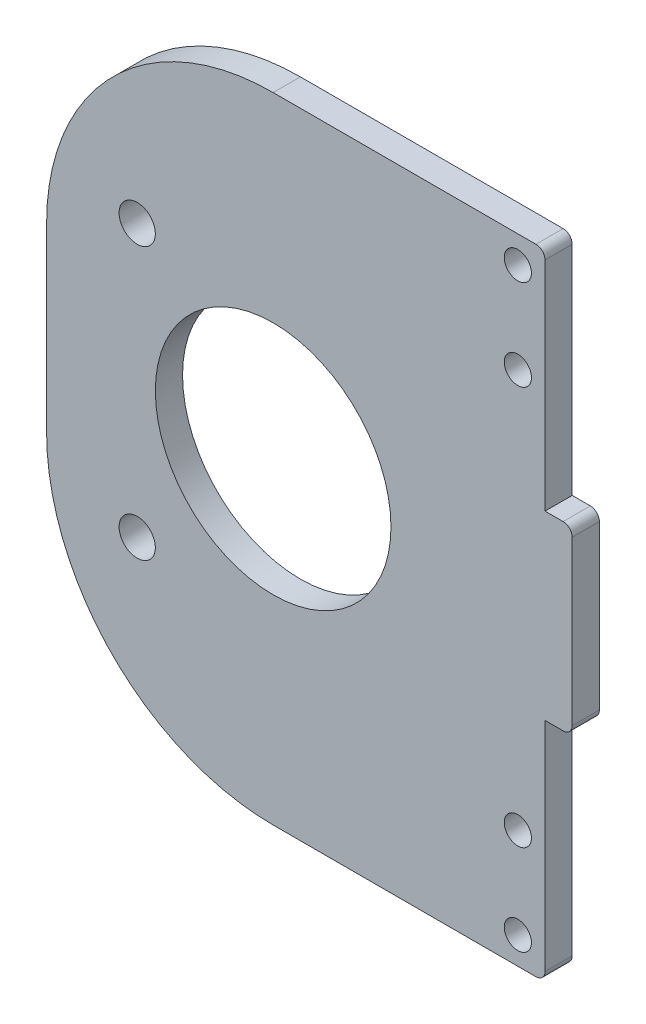
SolidWorks part; units mm, degrees
material "Thornel Mat VMA"
ref_plane "前视基准面" through (0, 0, 0) normal (0, 0, 1) x (1, 0, 0)
ref_plane "上视基准面" through (0, 0, 0) normal (0, 1, 0) x (1, 0, 0)
ref_plane "右视基准面" through (0, 0, 0) normal (1, 0, 0) x (0, 0, -1)
sketch "草图1" plane through (0, 0, 0) normal (0, 0, 1) x (1, 0, 0)
  line L1 (-27.5, -35) -> (27.5, -35)
  line L2 (-27.5, -35) -> (-27.5, 35)
  line L3 (-27.5, 35) -> (27.5, 35)
  line L4 (27.5, -35) -> (27.5, 35)
  line L5 (-27.5, -35) -> (27.5, 35) construction
  line L6 (-27.5, 35) -> (27.5, -35) construction
  point P0 (0, 0)
  dimension "D1" = 55
  dimension "D2" = 70
extrude "凸台-拉伸1" add sketch "草图1" along normal blind 3
sketch "草图3" plane through (0, 0, 0) normal (0, 0, -1) x (-1, 0, 0)
  line L0 (-27.5, 0) -> (27.5, 0) construction
  line L1 (-27.5, -35) -> (-27.5, 35) construction
  line L2 (27.5, 35) -> (27.5, -35) construction
  circle A0 centre (2.5, 0) radius 13
  dimension "D1" = 26
  dimension "D2" = 30
extrude "切除-拉伸1" cut sketch "草图3" against normal through all
sketch "草图4" plane through (0, 0, 3) normal (0, 0, 1) x (1, 0, 0)
  line L0 (-27.5, 0) -> (27.5, 0) construction
  line L1 (-27.5, 35) -> (-27.5, -35) construction
  line L2 (27.5, -35) -> (27.5, 35) construction
  line L3 (27.5, 35) -> (-27.5, 35) construction
  circle A0 centre (24.5, 32) radius 1.5
  circle A1 centre (24.5, 22) radius 1.5
  circle A2 centre (24.5, -22) radius 1.5
  circle A3 centre (24.5, -32) radius 1.5
  dimension "D3" = 3
  dimension "D1" = 3
  dimension "D2" = 3
  dimension "D4" = 10
extrude "切除-拉伸2" cut sketch "草图4" against normal through all
sketch "草图5" plane through (0, 0, 3) normal (0, 0, 1) x (1, 0, 0)
  line L0 (-27.5, 0) -> (27.5, 0) construction
  line L1 (-27.5, 35) -> (-27.5, -35) construction
  line L2 (27.5, -35) -> (27.5, 35) construction
  line L4 (27.5, -10) -> (30.5, -10)
  line L5 (27.5, -10) -> (27.5, 10)
  line L6 (27.5, 10) -> (30.5, 10)
  line L7 (30.5, -10) -> (30.5, 10)
  line L8 (27.5, -10) -> (30.5, 10) construction
  line L9 (27.5, 10) -> (30.5, -10) construction
  point P6 (29, 0)
  dimension "D1" = 3
  dimension "D2" = 20
extrude "凸台-拉伸2" add sketch "草图5" against normal blind 3
fillet "圆角1" radius 1 4 edges at (27.5, 35, 1.5) (27.5, -35, 1.5) (30.5, 10, 1.5) (30.5, -10, 1.5)
fillet "圆角2" radius 25 2 edges at (-27.5, -35, 1.5) (-27.5, 35, 1.5)
sketch "草图6" plane through (0, 0, 0) normal (0, 0, -1) x (-1, 0, 0)
  line L0 (-30.5, 0) -> (27.5, 0) construction
  line L1 (-30.5, -9) -> (-30.5, 9) construction
  line L2 (27.5, 10) -> (27.5, -10) construction
  line L3 (2.5, 13) -> (2.5, -13) construction
  circle A0 centre (2.5, 0) radius 13 construction
  circle A1 centre (17.5, 15) radius 2
  circle A2 centre (17.5, -15) radius 2
  dimension "D3" = 4
  dimension "D1" = 15
  dimension "D2" = 15
extrude "切除-拉伸3" cut sketch "草图6" against normal through all
